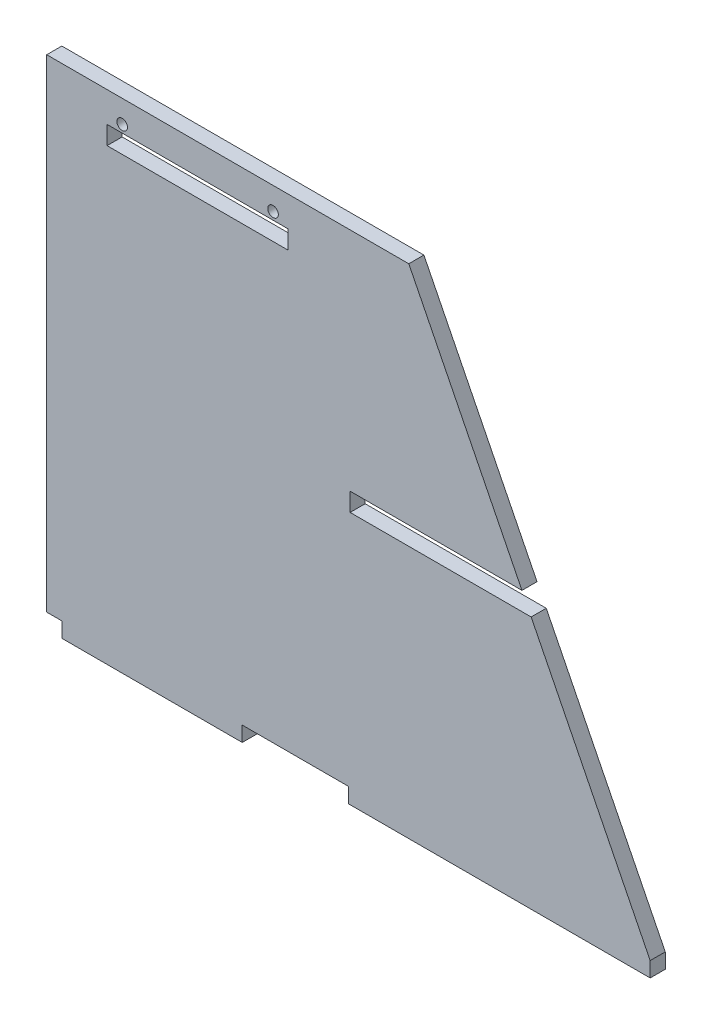
SolidWorks part; units mm, degrees
ref_plane "Front Plane" through (0, 0, 0) normal (0, 0, 1) x (1, 0, 0)
ref_plane "Top Plane" through (0, 0, 0) normal (0, 1, 0) x (1, 0, 0)
ref_plane "Right Plane" through (0, 0, 0) normal (1, 0, 0) x (0, 0, -1)
sketch "Sketch1" plane through (0, 0, 0) normal (0, 0, 1) x (1, 0, 0)
  line L0 (0, 0) -> (200, 0)
  line L5 (0, 0) -> (0, 160)
  line L6 (5, 0) -> (64.8, 0)
  line L7 (5, 0) -> (5, -5)
  line L8 (5, -5) -> (64.8, -5)
  line L9 (64.8, 0) -> (64.8, -5)
  line L10 (200, 0) -> (100, 0)
  line L11 (200, 0) -> (200, -5)
  line L12 (200, -5) -> (100, -5)
  line L13 (100, 0) -> (100, -5)
  line L14 (0, 160) -> (120, 160)
  line L15 (120, 160) -> (200, 0)
  dimension "D1" = 59.8
  dimension "D2" = 5
  dimension "D3" = 5
  dimension "D4" = 100
  dimension "D5" = 200
  dimension "D6" = 160
  dimension "D7" = 120
extrude "Boss-Extrude1" add sketch "Sketch1" along normal blind 5 contours L15 L14 L5 L0 | L0 L13 L12 L11 | L8 L9 L6 L7
sketch "Sketch2" plane through (0, 0, 5) normal (0, 0, 1) x (1, 0, 0)
  line L0 (0, 0) -> (0, 160) construction
  line L1 (20, 150) -> (80, 150)
  line L2 (20, 150) -> (20, 143.9)
  line L3 (20, 143.9) -> (80, 143.9)
  line L4 (80, 150) -> (80, 143.9)
  line L5 (0, 160) -> (120, 160) construction
  dimension "D1" = 6.1
  dimension "D2" = 60
  dimension "D3" = 20
  dimension "D4" = 10
extrude "Cut-Extrude1" cut sketch "Sketch2" against normal blind 5
sketch "Sketch3" plane through (0, 0, 5) normal (0, 0, 1) x (1, 0, 0)
  line L0 (80, 150) -> (20, 150) construction
  line L1 (0, 0) -> (0, 160) construction
  line L2 (50, -850) -> (50, 49150) construction
  circle A0 centre (25, 152.5) radius 1.75
  circle A1 centre (75, 152.5) radius 1.75
  point P10 (50, 150)
  dimension "D1" = 3.5
  dimension "D3" = 25
  dimension "D2" = 2.5
extrude "Cut-Extrude2" cut sketch "Sketch3" against normal blind 5
sketch "Sketch4" plane through (0, 0, 5) normal (0, 0, 1) x (1, 0, 0)
  line L0 (120, 160) -> (200, 0) construction
  line L1 (160.55, 78.9) -> (100.55, 78.9)
  line L2 (160.55, 78.9) -> (160.55, 85)
  line L3 (160.55, 85) -> (100.55, 85)
  line L4 (100.55, 78.9) -> (100.55, 85)
  line L5 (200, -5) -> (100, -5) construction
  dimension "D1" = 6.1
  dimension "D2" = 60
  dimension "D3" = 90
extrude "Cut-Extrude3" cut sketch "Sketch4" against normal blind 5
